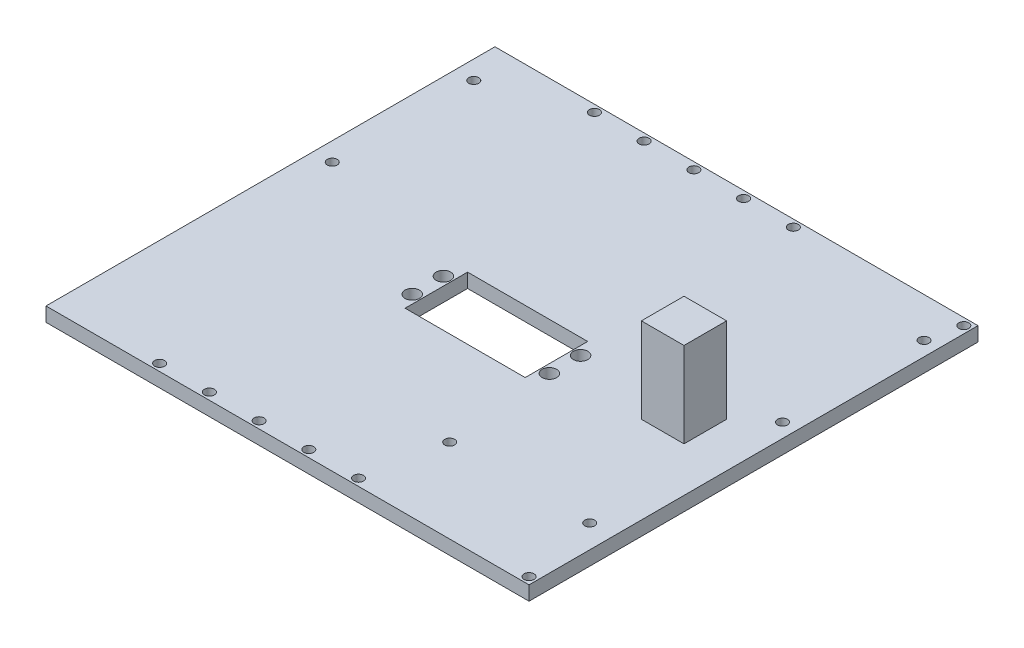
SolidWorks part; units mm, degrees
ref_plane "Front Plane" through (0, 0, 0) normal (0, 0, 1) x (1, 0, 0)
ref_plane "Top Plane" through (0, 0, 0) normal (0, 1, 0) x (1, 0, 0)
ref_plane "Right Plane" through (0, 0, 0) normal (1, 0, 0) x (0, 0, -1)
sketch "Sketch1" plane through (0, 0, 0) normal (0, 1, 0) x (1, 0, 0)
  line L1 (-85, -79) -> (85, -79)
  line L2 (-85, -79) -> (-85, 79)
  line L3 (-85, 79) -> (85, 79)
  line L4 (85, -79) -> (85, 79)
  line L5 (-85, -79) -> (85, 79) construction
  line L6 (-85, 79) -> (85, -79) construction
  line L7 (-21.13, -16.5) -> (21.14, -16.5)
  line L8 (-21.13, -16.5) -> (-21.13, 5.5)
  line L9 (-21.13, 5.5) -> (21.14, 5.5)
  line L10 (21.14, -16.5) -> (21.14, 5.5)
  line L11 (-21.13, -16.5) -> (21.14, 5.5) construction
  line L12 (-21.13, 5.5) -> (21.14, -16.5) construction
  circle A0 centre (82.5, 76.5) radius 1.75
  circle A1 centre (22.5, 76.5) radius 1.75
  circle A2 centre (5, 76.5) radius 1.75
  circle A3 centre (-12.5, 76.5) radius 1.75
  circle A4 centre (-30, 76.5) radius 1.75
  circle A5 centre (-47.5, 76.5) radius 1.75
  circle A6 centre (82.5, -76.5) radius 1.75
  circle A7 centre (22.5, -76.5) radius 1.75
  circle A8 centre (5, -76.5) radius 1.75
  circle A9 centre (-12.5, -76.5) radius 1.75
  circle A10 centre (-30, -76.5) radius 1.75
  circle A11 centre (-47.5, -76.5) radius 1.75
  circle A12 centre (80, 15.2) radius 1.75
  circle A13 centre (-78.46, 15.2) radius 1.75
  circle A14 centre (24.14, -11) radius 2.55
  circle A15 centre (24.14, 0) radius 2.55
  circle A16 centre (-24.13, 0) radius 2.55
  circle A17 centre (-24.13, -11) radius 2.55
  circle A18 centre (80, 65) radius 1.75
  circle A19 centre (-78.46, 65) radius 1.75
  circle A20 centre (76.8111, -49.4647) radius 1.75
  circle A21 centre (27.5411, -49.4647) radius 1.75
  point P0 (0, 0)
  point P44 (0.005, -5.5)
  dimension "D3" = 3.5
  dimension "D11" = 3.5
  dimension "D16" = 5.1
  dimension "D22" = 3.5
  dimension "D10" = 3.5
  dimension "D1" = 170
  dimension "D2" = 158
  dimension "D4" = 2.5
  dimension "D5" = 2.5
  dimension "D9" = 5
  dimension "D12" = 49.27
  dimension "D17" = 48.27
  dimension "D18" = 11
  dimension "D19" = 48.27
  dimension "D20" = 11
  dimension "D21" = 60.86
  dimension "D23" = 14
  dimension "D25" = 0
  dimension "D26" = 24.135
  dimension "D28" = 22
  dimension "D29" = 42.27
  dimension "D6" = 2
  dimension "D7" = 5
  dimension "D8" = 2
extrude "Boss-Extrude1" add sketch "Sketch1" along normal blind 5
sketch "Sketch2" plane through (0, 5, 0) normal (0, 1, 0) x (1, 0, 0)
  line L1 (54.3003, 6.2292) -> (69.3003, 6.2292)
  line L2 (54.3003, 6.2292) -> (54.3003, -8.7708)
  line L3 (54.3003, -8.7708) -> (69.3003, -8.7708)
  line L4 (69.3003, 6.2292) -> (69.3003, -8.7708)
  line L5 (54.3003, 6.2292) -> (69.3003, -8.7708) construction
  line L6 (54.3003, -8.7708) -> (69.3003, 6.2292) construction
  point P0 (61.8003, -1.2708)
  dimension "D1" = 15
  dimension "D2" = 15
extrude "Boss-Extrude2" add sketch "Sketch2" along normal blind 30
